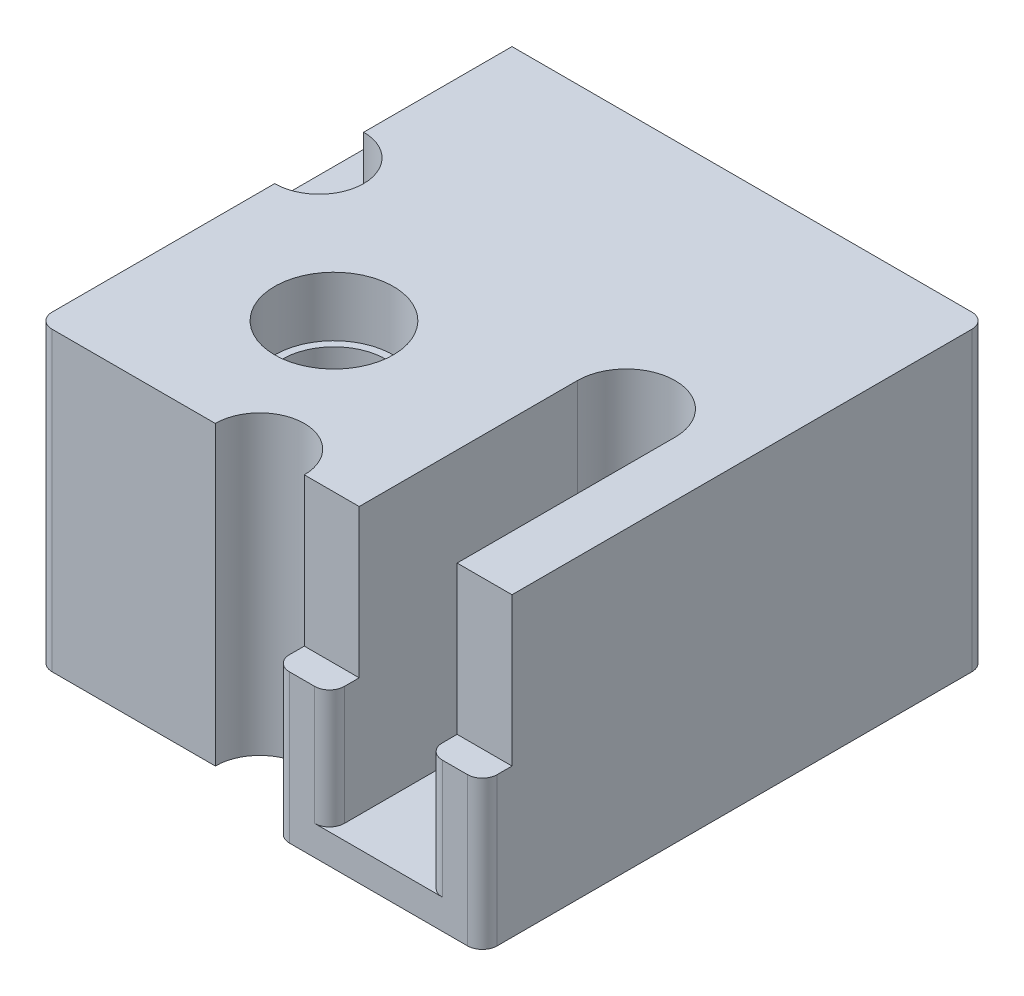
SolidWorks part; units mm, degrees
ref_plane "Front Plane" through (0, 0, 0) normal (0, 0, 1) x (1, 0, 0)
ref_plane "Top Plane" through (0, 0, 0) normal (0, 1, 0) x (1, 0, 0)
ref_plane "Right Plane" through (0, 0, 0) normal (1, 0, 0) x (0, 0, -1)
sketch "Sketch1" plane through (0, 0, 0) normal (0, 1, 0) x (1, 0, 0)
  line L1 (0, 0) -> (20.5, 0)
  line L2 (4.5, -5) -> (4.5, -16)
  line L3 (4.5, -16) -> (13.5, -16)
  line L6 (20.5, 0) -> (20.5, -17)
  line L7 (20.5, -17) -> (13.5, -17)
  line L8 (13.5, -16) -> (13.5, -17)
  line L9 (4.5, -5) -> (0, -5)
  line L10 (0, 0) -> (0, -5)
  dimension "D1" = 16
  dimension "D2" = 16
  dimension "D3" = 1
  dimension "D4" = 7
  dimension "D5" = 5
  dimension "D6" = 4.5
extrude "Boss-Extrude1" add sketch "Sketch1" along normal blind 10
sketch "Sketch4" plane through (0, 10, 0) normal (0, 1, 0) x (1, 0, 0)
  line L0 (4.5, -5) -> (4.5, -16) construction
  line L2 (4.5, -16) -> (13.5, -16) construction
  circle A0 centre (9.5, -11) radius 1.75
  dimension "D3" = 3.5
  dimension "D1" = 5
  dimension "D2" = 5
extrude "Cut-Extrude3" cut sketch "Sketch4" against normal blind 10
sketch "Sketch6" plane through (0, 10, 0) normal (0, 1, 0) x (1, 0, 0)
  circle A0 centre (9.5, -11) radius 2
  dimension "D1" = 4
extrude "Cut-Extrude5" cut sketch "Sketch6" against normal blind 2
sketch "Sketch7" plane through (0, 0, 0) normal (0, -1, 0) x (1, 0, 0)
  line L0 (0, 6.5) -> (4.5, 6.5) construction
  line L1 (4.5, 5) -> (4.5, 16) construction
  line L2 (0, 8) -> (4.5, 8)
  line L3 (0, 5) -> (4.5, 5)
  line L4 (0, 5) -> (4.5, 5) construction
  line L5 (0, 0) -> (0, 5) construction
  line L6 (12, 16) -> (12, 17) construction
  line L7 (4.5, 16) -> (13.5, 16) construction
  line L8 (10.5, 16) -> (10.5, 17)
  line L9 (13.5, 16) -> (13.5, 17)
  line L10 (13.5, 17) -> (20.5, 17) construction
  line L11 (13.5, 16) -> (13.5, 17) construction
  arc A0 (0, 8) -> (0, 5) centre (0, 6.5) ccw
  arc A1 (4.5, 5) -> (4.5, 8) centre (4.5, 6.5) ccw
  arc A2 (10.5, 16) -> (13.5, 16) centre (12, 16) ccw
  arc A3 (13.5, 17) -> (10.5, 17) centre (12, 17) ccw
  point P4 (2.25, 6.5)
  point P17 (12, 16.5)
  dimension "D1" = 3
  dimension "D2" = 3
extrude "Cut-Extrude6" cut sketch "Sketch7" against normal through all
sketch "Sketch8" plane through (0, 10, 0) normal (0, 1, 0) x (1, 0, 0)
  line L0 (20.5, -17) -> (20.5, 0) construction
  line L1 (13.5, -16) -> (20.5, -16)
  line L2 (13.5, -16) -> (13.5, -17)
  line L3 (13.5, -17) -> (20.5, -17)
  line L4 (20.5, -16) -> (20.5, -17)
  line L5 (4.5, -5) -> (0, -5)
  line L6 (4.5, -5) -> (4.5, 0)
  line L7 (4.5, 0) -> (0, 0)
  line L8 (0, -5) -> (0, 0)
  line L9 (13.5, -17) -> (20.5, -17) construction
  line L10 (0, -5) -> (4.5, -5) construction
  line L11 (4.5, -8) -> (4.5, -16) construction
  line L12 (4.5, -16) -> (10.5, -16) construction
  line L13 (13.5, -16) -> (13.5, -17) construction
extrude "Cut-Extrude7" cut sketch "Sketch8" against normal blind 5
sketch "Sketch9" plane through (0, 10, 0) normal (0, 1, 0) x (1, 0, 0)
  line L4 (17, -17) -> (17, -8.65) construction
  line L5 (15.35, -17) -> (15.35, -8.65)
  line L6 (18.65, -17) -> (18.65, -8.65)
  line L7 (13.5, -17) -> (20.5, -17) construction
  arc A2 (15.35, -17) -> (18.65, -17) centre (17, -17) ccw
  arc A3 (18.65, -8.65) -> (15.35, -8.65) centre (17, -8.65) ccw
  point P11 (17, -12.825)
  dimension "D1" = 1.65
  dimension "D2" = 8.35
extrude "Cut-Extrude8" cut sketch "Sketch9" against normal blind 9
fillet "Fillet6" radius 0.5 8 edges at (4.5, 5, 16) (20.5, 5, 0) (13.5, 2.5, 17) (20.5, 2.5, 17) (0, 2.5, 0) (0, 2.5, 5) (18.65, 3, 17) (15.35, 3, 17)
